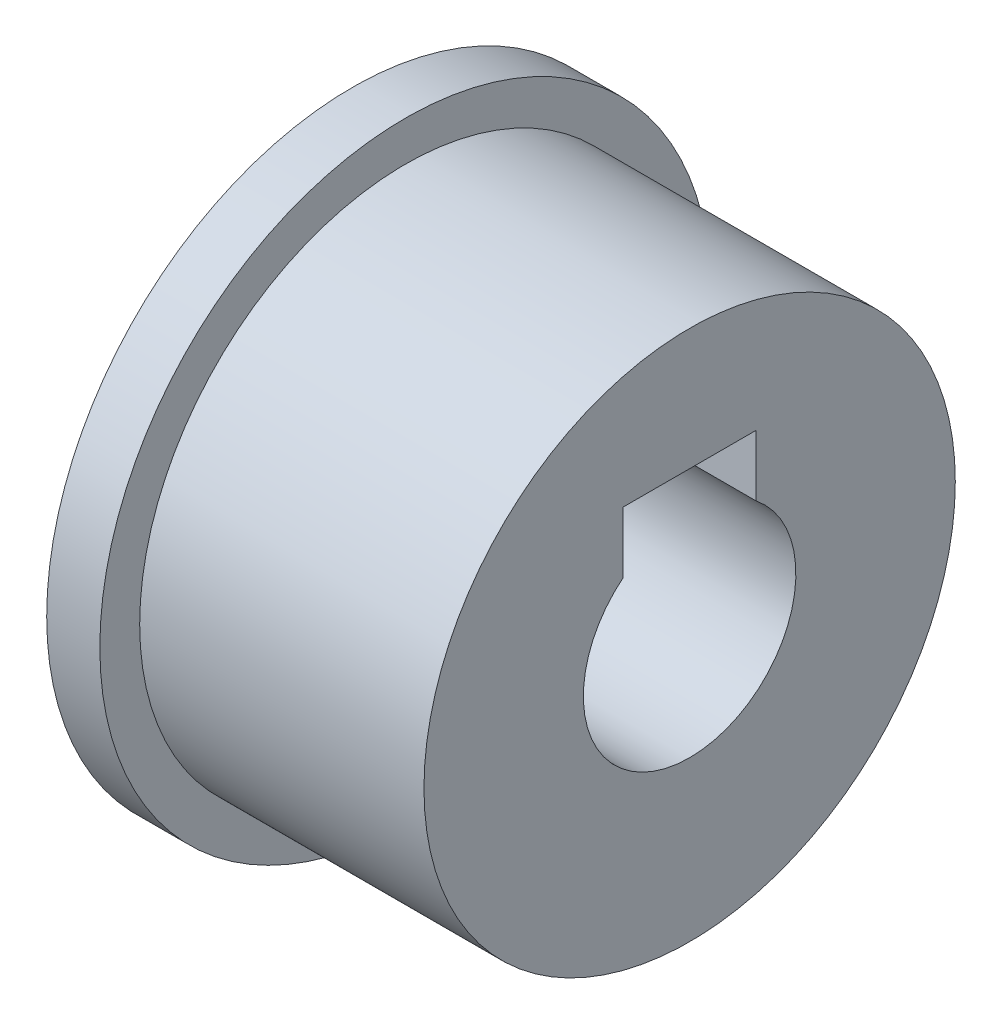
SolidWorks part; units mm, degrees
ref_plane "Front Plane" through (0, 0, 0) normal (0, 0, 1) x (1, 0, 0)
ref_plane "Top Plane" through (0, 0, 0) normal (0, 1, 0) x (1, 0, 0)
ref_plane "Right Plane" through (0, 0, 0) normal (1, 0, 0) x (0, 0, -1)
sketch "Sketch1" plane through (0, 0, 0) normal (1, 0, 0) x (0, 0, -1)
  line L0 (0, 0) -> (0, 4.2725) construction
  line L1 (-2.5, 3.1225) -> (2.5, 3.1225) construction
  line L2 (-2.5, 5.4225) -> (2.5, 5.4225)
  line L3 (-2.5, 5.4225) -> (-2.5, 3.1225)
  line L5 (2.5, 5.4225) -> (2.5, 3.1225)
  line L6 (-2.5, 5.4225) -> (2.3722, 3.1813) construction
  line L7 (-2.5, 3.1225) -> (2.5, 5.4225) construction
  arc A0 (-2.5, 3.1225) -> (2.5, 3.1225) centre (0, 0) ccw
  circle A1 centre (0, 0) radius 10
  dimension "D1" = 8
  dimension "D4" = 20
  dimension "D2" = 5
  dimension "D3" = 2.3
extrude "Boss-Extrude1" add sketch "Sketch1" along normal blind 12.7
sketch "Sketch2" plane through (0, 0, 0) normal (-1, 0, 0) x (0, 0, 1)
  circle A0 centre (0, 0) radius 11.5
  circle A1 centre (0, 0) radius 10
  circle A2 centre (0, 0) radius 10
  dimension "D2" = 23
  dimension "D1" = 0
extrude "Boss-Extrude2" add sketch "Sketch2" against normal blind 2
